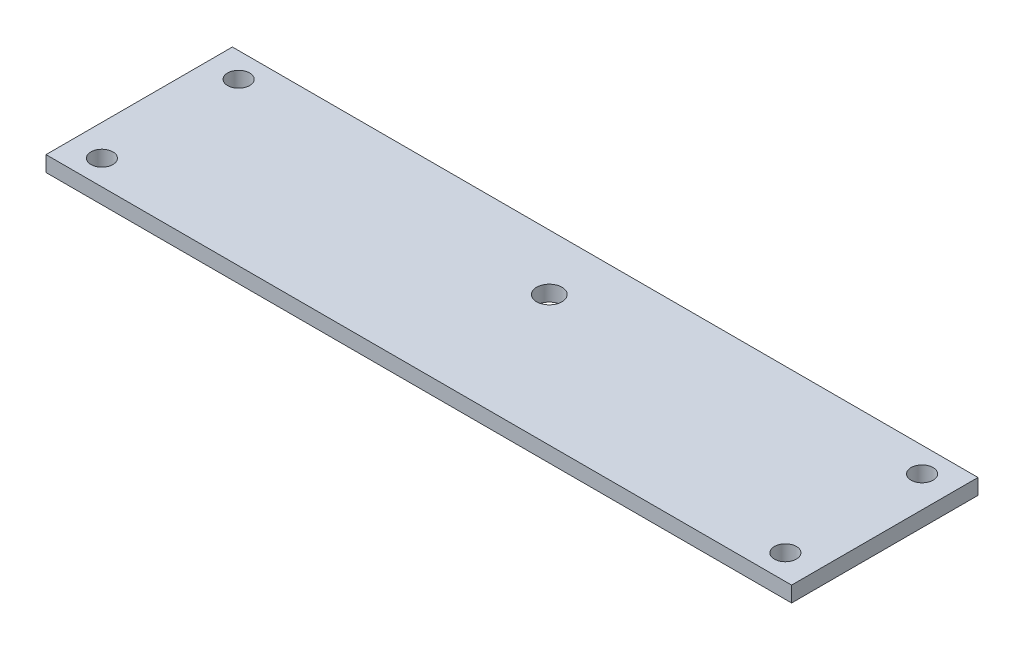
SolidWorks part; units mm, degrees
ref_plane "Front Plane" through (0, 0, 0) normal (0, 0, 1) x (1, 0, 0)
ref_plane "Top Plane" through (0, 0, 0) normal (0, 1, 0) x (1, 0, 0)
ref_plane "Right Plane" through (0, 0, 0) normal (1, 0, 0) x (0, 0, -1)
sketch "Sketch1" plane through (0, 0, 0) normal (0, 0, 1) x (1, 0, 0)
  line L0 (0, 1.5875) -> (0, -1.5875)
  line L1 (-76.2, 0) -> (76.2, 0) construction
  point P6 (0, 0)
  dimension "Width" = 152.4
  dimension "Thk" = 3.175
sketch "Sketch2" plane through (0, 0, 0) normal (1, 0, 0) x (0, 0, -1)
  line L0 (19.05, 0) -> (-19.05, 0)
  point P4 (0, 0)
  dimension "Length" = 38.1
sketch "Sketch3" plane through (0, 0, 0) normal (0, 0, 1) x (1, 0, 0)
  line L1 (76.2, 1.5875) -> (-76.2, 1.5875)
  line L2 (76.2, 1.5875) -> (76.2, -1.5875)
  line L3 (76.2, -1.5875) -> (-76.2, -1.5875)
  line L4 (-76.2, 1.5875) -> (-76.2, -1.5875)
  line L5 (76.2, 1.5875) -> (-76.2, -1.5875) construction
  line L6 (76.2, -1.5875) -> (-76.2, 1.5875) construction
  point P0 (0, 0)
extrude "Boss-Extrude1" add sketch "Sketch3" along normal up to vertex (19.05 mm away) and the other way up to vertex (19.05 mm away) up to point (0, 0, 19.05) other way up to point (0, 0, -19.05)
sketch "Sketch4" plane through (0, 1.5875, 0) normal (0, 1, 0) x (1, 0, 0)
  line L0 (-69.85, 13.97) -> (-69.85, -13.97) construction
  line L1 (-76.2, -19.05) -> (-76.2, 19.05) construction
  point P0 (-69.85, 13.97)
  point P1 (-69.85, -13.97)
  point P6 (-76.2, 0)
  point P7 (-69.85, 0)
  dimension "D1" = 27.94
  dimension "D2" = 6.35
hole_wizard "#8 Clearance Hole1" positions "Sketch5" profile "Sketch7" hole size "#8" standard "ANSI Inch" end condition through all
sketch "Sketch5" plane through (0, 1.5875, 0) normal (0, 1, 0) x (1, 0, 0)
  point P0 (-69.85, 13.97)
  point P3 (-69.85, -13.97)
sketch "Sketch7" plane through (-69.85, 1.5875, -13.97) normal (1, 0, 0) x (0, 0, 1)
  line L0 (0, 0) -> (0, 3.175)
  line L1 (0, 3.175) -> (2.2479, 3.175)
  line L2 (2.2479, 3.175) -> (2.2479, 0)
  line L5 (2.2479, 0) -> (0, 0)
  line L11 (0, -6.35) -> (0, 107.95) construction
  dimension "Thru Hole Dia." = 4.4958
  dimension "Thru Hole Depth" = 3.175
mirror "Mirror1" about plane through (0, 0, 0) normal (1, 0, 0) of "#8 Clearance Hole1"
sketch "Sketch8" plane through (0, 1.5875, 0) normal (0, 1, 0) x (1, 0, 0)
  line L0 (0, -1.7463) -> (0, 1.7463) construction
  line L1 (76.2, 19.05) -> (-76.2, 19.05) construction
  point P0 (0, 7.62)
  dimension "D1" = 11.43
hole_wizard "#6 (0.204) Diameter Hole1" positions "Sketch9" profile "Sketch11" hole size "#6" standard "ANSI Inch" end condition through all
sketch "Sketch9" plane through (0, 1.5875, 0) normal (0, 1, 0) x (1, 0, 0)
  point P0 (0, 7.62)
sketch "Sketch11" plane through (0, 1.5875, -7.62) normal (1, 0, 0) x (0, 0, 1)
  line L0 (0, 0) -> (0, 3.175)
  line L1 (0, 3.175) -> (2.5908, 3.175)
  line L2 (2.5908, 3.175) -> (2.5908, 0)
  line L5 (2.5908, 0) -> (0, 0)
  line L11 (0, -6.35) -> (0, 107.95) construction
  dimension "Thru Hole Dia." = 5.1816
  dimension "Thru Hole Depth" = 3.175
